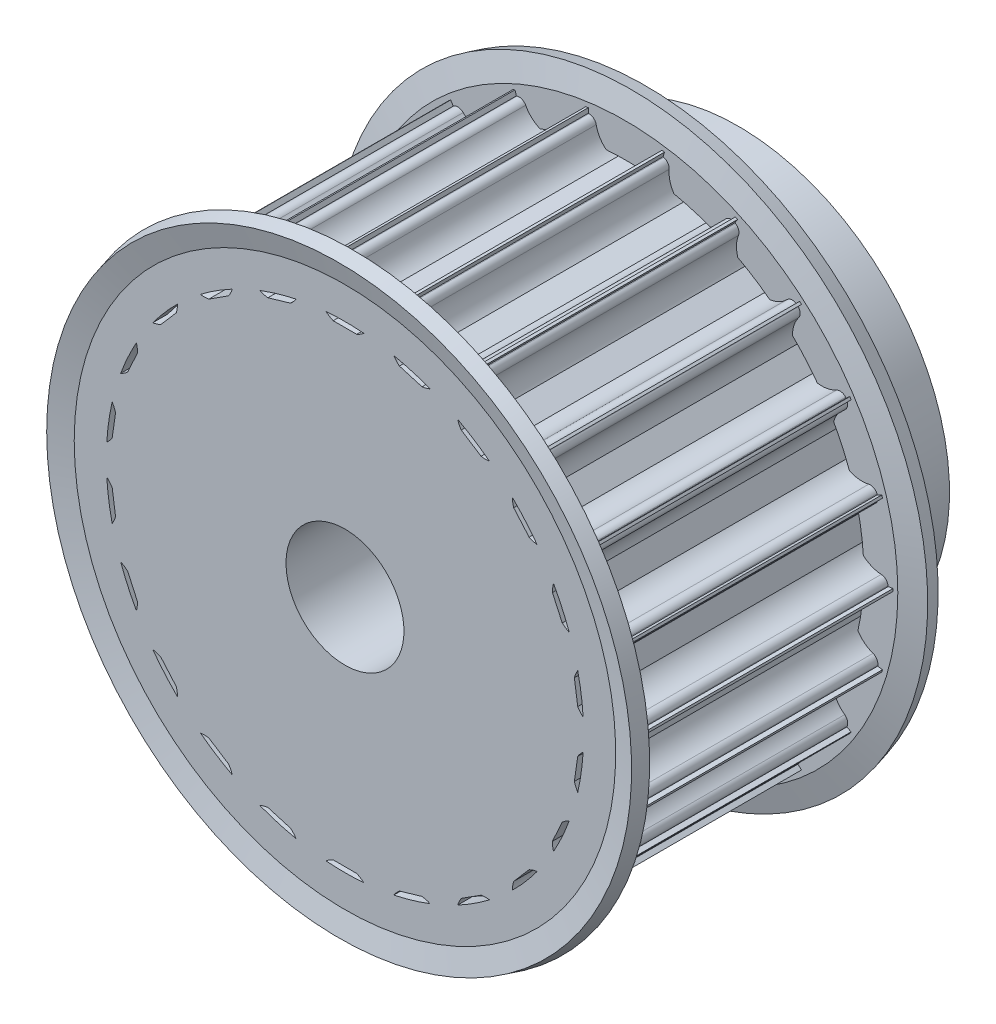
SolidWorks part; units mm, degrees
ref_plane "Front Plane" through (0, 0, 0) normal (0, 0, 1) x (1, 0, 0)
ref_plane "Top Plane" through (0, 0, 0) normal (0, 1, 0) x (1, 0, 0)
ref_plane "Right Plane" through (0, 0, 0) normal (1, 0, 0) x (0, 0, -1)
ref_axis "Axis1" through (0, 0, -88.99) along (0, 0, 1)
sketch "Sketch2" plane through (0, 0, 0) normal (1, 0, 0) x (0, 0, -1)
  line L0 (0, 6) -> (0, 27.25)
  line L1 (0, 27.25) -> (30, 27.25)
  line L2 (30, 27.25) -> (30, 21.5)
  line L3 (30, 21.5) -> (40, 21.5)
  line L4 (40, 21.5) -> (40, 6)
  line L5 (40, 6) -> (0, 6)
  line L6 (88.99, 0) -> (-88.99, 0) construction
  dimension "D1" = 6
  dimension "D2" = 21.25
  dimension "D3" = 30
  dimension "D4" = 10
  dimension "D5" = 15.5
revolve "Revolve1" add sketch "Sketch2" angle 360 about axis through (0, 0, -88.99) along (0, 0, 1)
sketch "Sketch3" plane through (0, 0, 0) normal (0, 0, 1) x (1, 0, 0)
  line L0 (3.6742, 26.5) -> (3.75, 26.5)
  line L1 (-3.75, 28.5) -> (3.75, 28.5)
  line L2 (-3.75, 28.5) -> (-3.75, 26.5)
  line L3 (-3.75, 26.5) -> (-3.6742, 26.5)
  line L4 (3.75, 28.5) -> (3.75, 26.5)
  line L5 (-1.199, 23.75) -> (1.199, 23.75)
  arc A0 (-2.9394, 25.9) -> (-1.199, 23.75) centre (0, 26.5) ccw
  arc A1 (-2.9394, 25.9) -> (-3.6742, 26.5) centre (-3.6742, 25.75) ccw
  arc A2 (2.9394, 25.9) -> (3.6742, 26.5) centre (3.6742, 25.75) cw
  arc A3 (1.199, 23.75) -> (2.9394, 25.9) centre (0, 26.5) ccw
  point P10 (-3, 26.5)
  point P13 (3, 26.5)
  dimension "D1" = 3
  dimension "D5" = 0.75
  dimension "D6" = 0.75
  dimension "D2" = 2
  dimension "D3" = 7.5
  dimension "D4" = 26.5
  dimension "D7" = 2.75
extrude "Cut-Extrude1" cut sketch "Sketch3" against normal through all and the other way through all
pattern_circular "CirPattern1" count 22 over 360 about axis through (0, 0, 0) along (0, 0, 1) of "Cut-Extrude1"
sketch "Sketch4" plane through (0, 0, 0) normal (1, 0, 0) x (0, 0, -1)
  line L0 (-0.592, 29.7525) -> (0.0511, 27.3525) construction
  line L1 (0, 24.2797) -> (1.5, 24.2797)
  line L2 (0, 24.2797) -> (0, 27.7407) construction
  line L3 (0, 27.7407) -> (1.5, 27.7407) construction
  line L4 (1.5, 24.2797) -> (1.5, 27.7407)
  line L5 (-0.592, 29.7525) -> (0.8569, 30.1407)
  line L6 (0.0511, 27.3525) -> (1.5, 27.7407) construction
  line L7 (0.8569, 30.1407) -> (1.5, 27.7407)
  line L10 (0, 26.9907) -> (30, 26.9907) construction
  line L11 (0, 24.2797) -> (0, 27.5433)
  line L12 (0, 27.5433) -> (-0.592, 29.7525)
  line L13 (15, 26.9539) -> (15, 38.6051) construction
  line L14 (30, 26.9539) -> (0, 26.9539) construction
  line L15 (30, 24.2797) -> (28.5, 24.2797)
  line L16 (28.5, 24.2797) -> (28.5, 27.7407)
  line L17 (29.1431, 30.1407) -> (28.5, 27.7407)
  line L18 (30.592, 29.7525) -> (29.1431, 30.1407)
  line L19 (30, 27.5433) -> (30.592, 29.7525)
  line L20 (30, 24.2797) -> (30, 27.5433)
  dimension "D1" = 1.5
  dimension "D2" = 0.75
  dimension "D3" = 195
  dimension "D4" = 2.4
  dimension "D5" = 1.5
revolve "Revolve2" add sketch "Sketch4" angle 360 about axis through (0, 0, -88.99) along (0, 0, 1)
